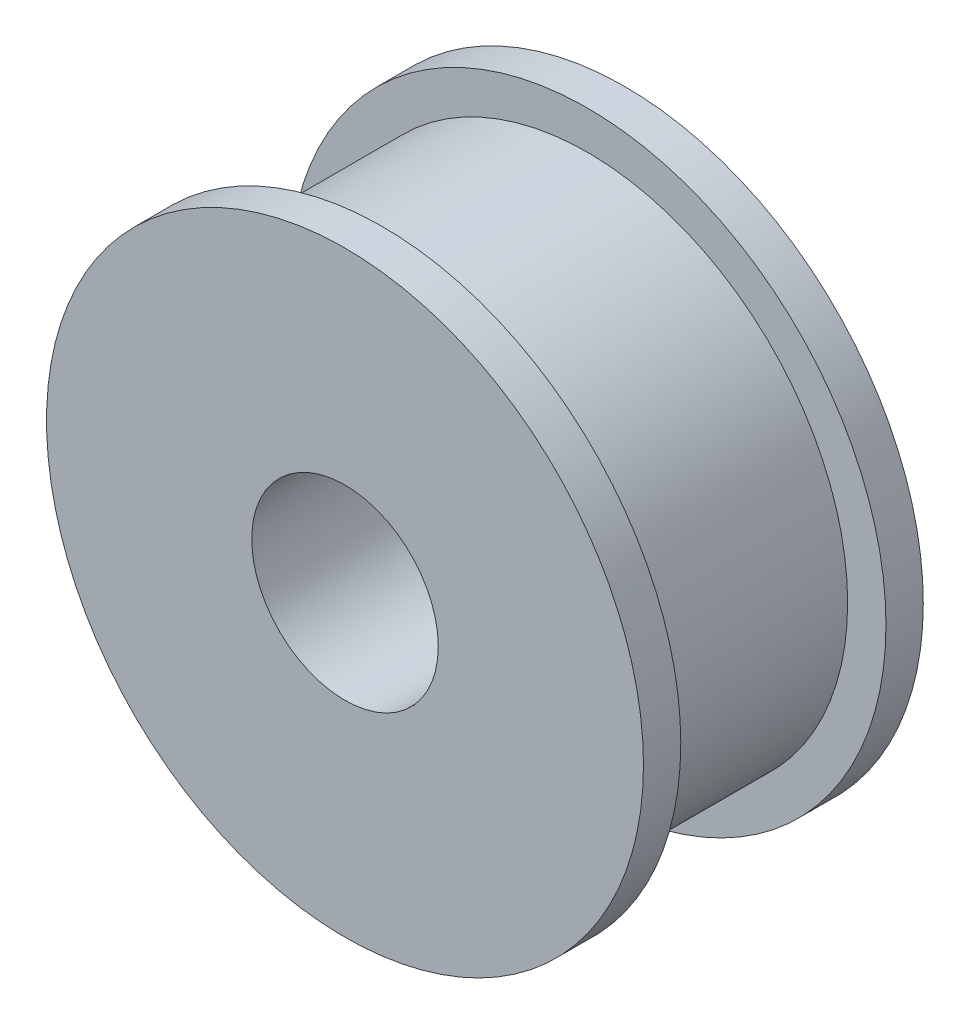
SolidWorks part; units mm, degrees
ref_plane "前视基准面" through (0, 0, 0) normal (0, 0, 1) x (1, 0, 0)
ref_plane "上视基准面" through (0, 0, 0) normal (0, 1, 0) x (1, 0, 0)
ref_plane "右视基准面" through (0, 0, 0) normal (1, 0, 0) x (0, 0, -1)
sketch "草图1" plane through (0, 0, 0) normal (0, 0, 1) x (1, 0, 0)
  circle A0 centre (0, 0) radius 16
  dimension "D1" = 32
extrude "凸台-拉伸1" add sketch "草图1" along normal blind 2 contours A0
sketch "草图2" plane through (0, 0, 2) normal (0, 0, 1) x (1, 0, 0)
  circle A0 centre (0, 0) radius 13.945
  dimension "D1" = 27.89
extrude "凸台-拉伸2" add sketch "草图2" along normal blind 11
sketch "草图3" plane through (0, 0, 13) normal (0, 0, 1) x (1, 0, 0)
  circle A0 centre (0, 0) radius 16
  dimension "D1" = 32
extrude "凸台-拉伸3" add sketch "草图3" along normal blind 2
sketch "草图4" plane through (0, 0, 15) normal (0, 0, 1) x (1, 0, 0)
  circle A0 centre (0, 0) radius 5
  dimension "D1" = 10
extrude "切除-拉伸1" cut sketch "草图4" against normal blind 15
